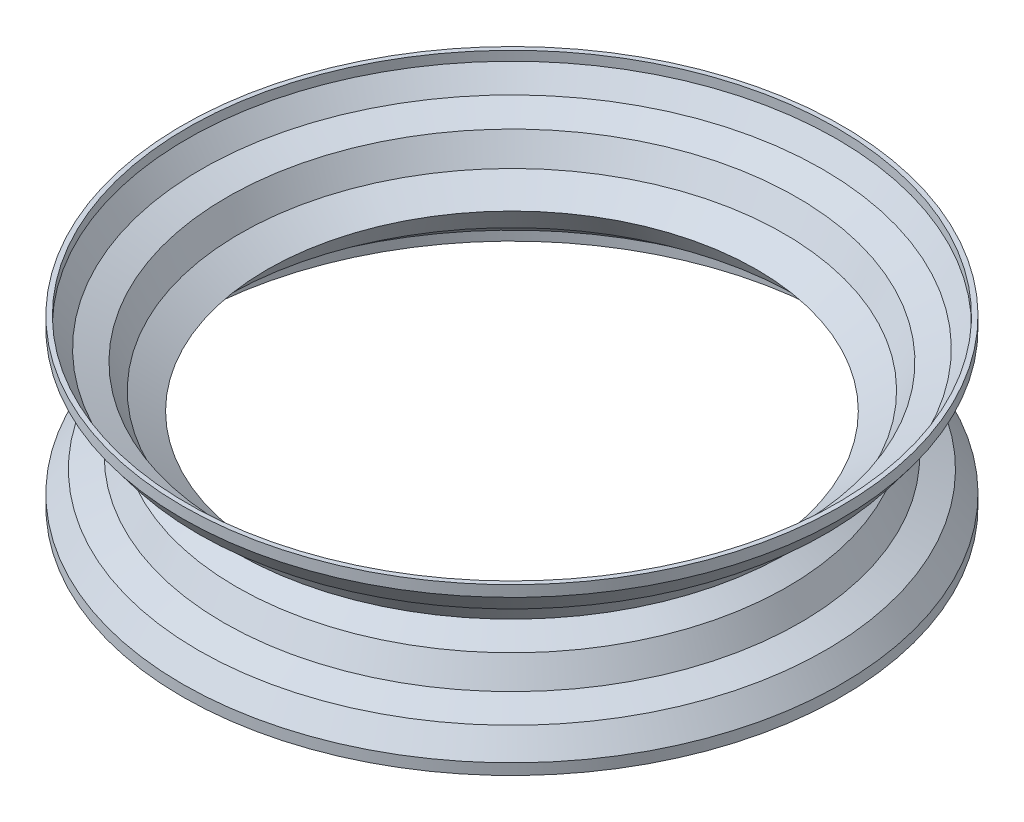
SolidWorks part; units mm, degrees
ref_plane "정면" through (0, 0, 0) normal (0, 0, 1) x (1, 0, 0)
ref_plane "윗면" through (0, 0, 0) normal (0, 1, 0) x (1, 0, 0)
ref_plane "우측면" through (0, 0, 0) normal (1, 0, 0) x (0, 0, -1)
sketch "스케치1" plane through (0, 0, 0) normal (0, 1, 0) x (1, 0, 0)
  circle A7 centre (0, 0) radius 35.8938
  dimension "D2" = 71.7876
extrude "보스-돌출1" add sketch "스케치1" along normal blind 1.2
ref_plane "평면1" through (0, 9, 0) normal (0, -1, 0) x (-1, 0, 0)
sketch "스케치3" plane through (0, 9, 0) normal (0, -1, 0) x (-1, 0, 0)
  circle A0 centre (0, 0) radius 27.5887
  dimension "D1" = 55.1775
sketch "스케치4" plane through (0, 0, 0) normal (1, 0, 0) x (0, 0, -1)
  line L0 (-29.665, 7.05) -> (-30.0073, 7.4145) construction
  line L1 (-27.5887, 9) -> (27.5887, 9) construction
  line L2 (0, 9) -> (0, 1.2) construction
  line L3 (35.8938, 1.2) -> (-35.8938, 1.2) construction
  line L4 (-35.8938, 1.2) -> (-34.1598, 3.5145)
  line L5 (-34.1598, 3.5145) -> (-31.399, 4.7355)
  line L6 (-30.0073, 7.4145) -> (-31.399, 4.7355)
  line L7 (-30.0073, 7.4145) -> (-27.5887, 9)
  line L8 (0, 9) -> (-27.5887, 9) construction
  line L9 (-31.7413, 5.1) -> (-31.399, 4.7355) construction
  line L10 (-31.7413, 5.1) -> (-35.8938, 1.2) construction
  line L11 (-31.7413, 5.1) -> (-27.5887, 9) construction
  line L12 (-34.1598, 3.5145) -> (-33.8175, 3.15) construction
  line L13 (0, 9) -> (27.5887, 9) construction
  line L14 (-27.5887, 9) -> (0, 9)
  line L15 (0, 9) -> (0, 1.2)
  line L16 (-35.8938, 1.2) -> (0, 1.2)
  dimension "D1" = 55.1775
  dimension "D2" = 0.5
revolve "회전1" add sketch "스케치4" angle 360 about L15
mirror "대칭 복사1" about plane through (0, 9, 27.5887) normal (0, 1, 0) of "보스-돌출1", "회전1"
shell "쉘1" thickness 0.5
